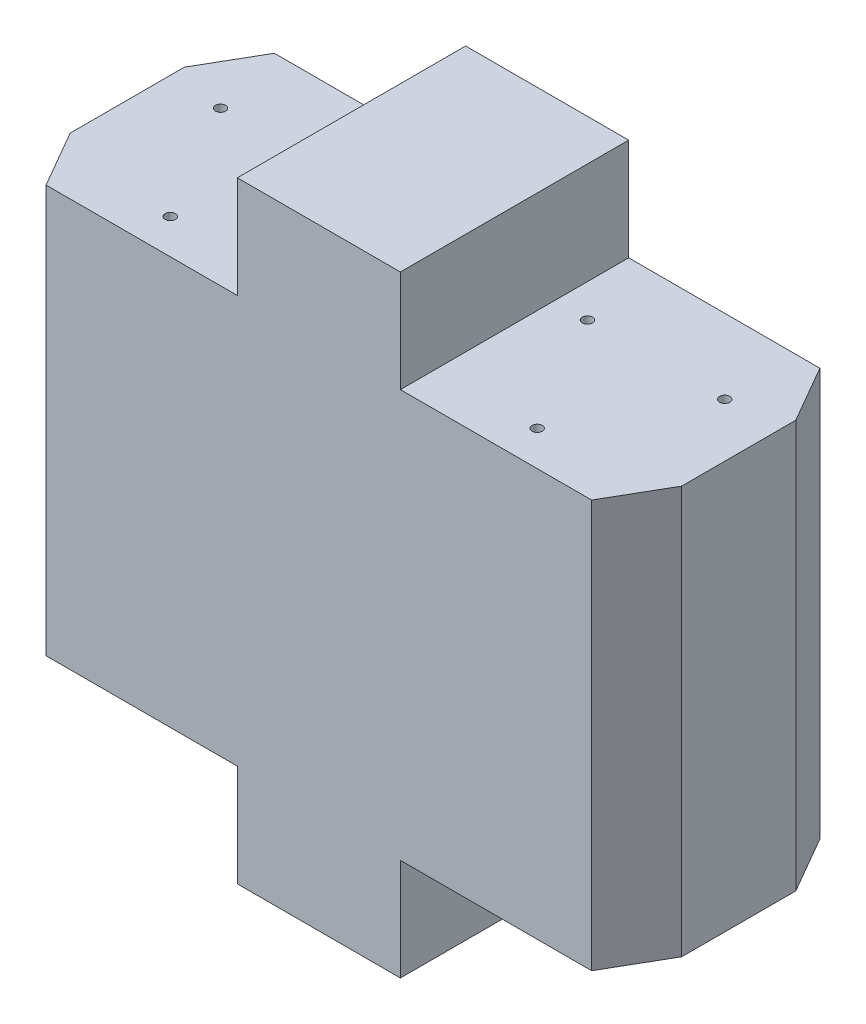
SolidWorks part; units mm, degrees
material "PLA"
ref_plane "Front" through (0, 0, 0) normal (0, 0, 1) x (1, 0, 0)
ref_plane "Top" through (0, 0, 0) normal (0, 1, 0) x (1, 0, 0)
ref_plane "Right" through (0, 0, 0) normal (1, 0, 0) x (0, 0, -1)
other "Configuration Table"
sketch "Esquisse1" plane through (0, 0, 0) normal (0, 1, 0) x (1, 0, 0)
  line L0 (-75, 7) -> (-66.9171, 21)
  line L1 (-75, 7) -> (75, 7)
  line L2 (-75, 7) -> (-75, -7)
  line L3 (-75, -7) -> (75, -7)
  line L4 (75, 7) -> (75, -7)
  line L5 (-75, 7) -> (75, -7) construction
  line L6 (-75, -7) -> (75, 7) construction
  line L7 (-66.9171, 21) -> (66.9171, 21)
  line L8 (66.9171, 21) -> (75, 7)
  point P0 (0, 0)
  dimension "D1" = 14
  dimension "D2" = 150
  dimension "D3" = 60
  dimension "D4" = 14
extrude "Boss.-Extru.1" add sketch "Esquisse1" along normal blind 100 contours L4 L1 L2 L3 | L8 L7 L0 L1
mirror "Symétrie1" about plane through (0, 100, 7) normal (0, 0, -1) of "Boss.-Extru.1"
sketch "Esquisse3" plane through (0, 0, 0) normal (0, -1, 0) x (1, 0, 0)
  line L0 (-66.9171, 35) -> (66.9171, 35) construction
  line L1 (20, -21) -> (-20, -21)
  line L2 (20, -21) -> (20, 35)
  line L3 (20, 35) -> (-20, 35)
  line L4 (-20, -21) -> (-20, 35)
  line L5 (20, -21) -> (-20, 35) construction
  line L6 (20, 35) -> (-20, -21) construction
  line L7 (-75, -7) -> (-75, 21) construction
  line L8 (-66.9171, -21) -> (66.9171, -21) construction
  point P0 (0, 7)
  point P10 (-75, 7)
  point P15 (0, -21)
  dimension "D1" = 40
extrude "Boss.-Extru.2" add sketch "Esquisse3" along normal blind 25 and the other way offset from surface (125 mm away) 25 other way up to face at (0, 100, 7)
shell "Coque1" thickness 4
sketch "Esquisse2" plane through (0, 100, 0) normal (0, 1, 0) x (1, 0, 0)
  line L0 (-75, -7) -> (-45, -7) construction
  line L5 (45, -7) -> (45, -26.45) construction
  line L6 (45, -7) -> (28.1558, 2.725) construction
  line L7 (-75, 7) -> (-75, -21) construction
  line L8 (75, 7) -> (75, -21) construction
  line L9 (-45, -7) -> (-15, -7) construction
  line L10 (45, -7) -> (75, -7) construction
  line L11 (15, -7) -> (45, -7) construction
  line L16 (45, -7) -> (61.8442, 2.725) construction
  line L18 (-15, -7) -> (15, -7) construction
  circle A8 centre (45, -7) radius 19.45
  circle A9 centre (45, -26.45) radius 1.25
  circle A10 centre (61.8442, 2.725) radius 1.25
  circle A11 centre (28.1558, 2.725) radius 1.25
  dimension "D1" = 38.9
  dimension "D3" = 120
  dimension "D2" = 2.5
  dimension "D4" = 120
extrude "Enlèv. mat.-Extru.1" cut sketch "Esquisse2" against normal through all
mirror "Symétrie2" about plane through (0, 0, 0) normal (1, 0, 0) of "Enlèv. mat.-Extru.1"
